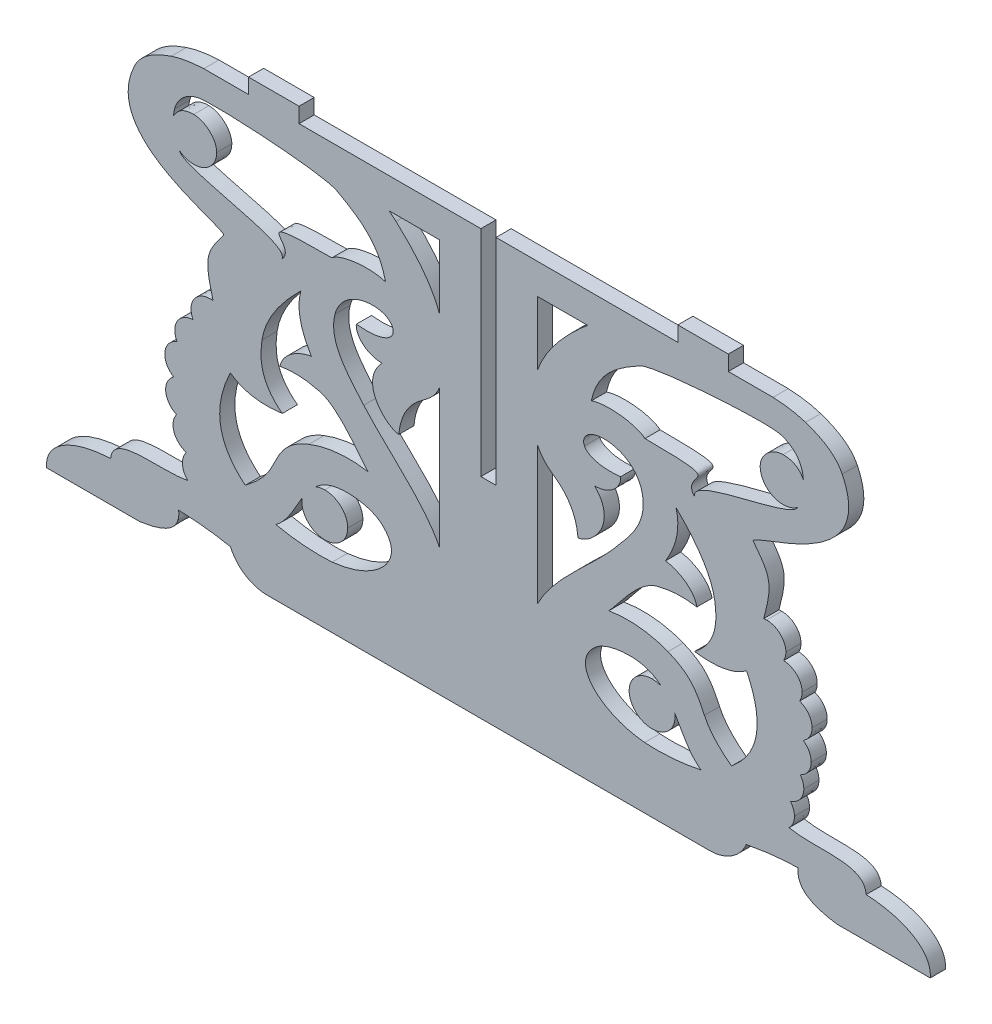
SolidWorks part; units mm, degrees
ref_plane "Plano frontal" through (0, 0, 0) normal (0, 0, 1) x (1, 0, 0)
ref_plane "Plano superior" through (0, 0, 0) normal (0, 1, 0) x (1, 0, 0)
ref_plane "Plano direito" through (0, 0, 0) normal (1, 0, 0) x (0, 0, -1)
sketch "Model" plane through (0, 0, 0) normal (0, 0, 1) x (1, 0, 0)
  line L0 (-58.0295, -71.5532) -> (-45.7155, -71.5532)
  line L1 (46.2957, -71.5532) -> (58.6097, -71.5532)
  line L2 (37.859, -15.5493) -> (31.9567, -15.5493)
  line L3 (31.9567, -15.5493) -> (31.9567, -13.5542)
  line L4 (31.9567, -13.5542) -> (25.2901, -13.5542)
  line L5 (25.2901, -13.5542) -> (25.2901, -15.5493)
  line L6 (25.2901, -15.5493) -> (1.2901, -15.5493)
  line L7 (1.2901, -15.5493) -> (1.2901, -43.8921)
  line L8 (1.2901, -43.8921) -> (-0.7099, -43.8921)
  line L9 (-0.7099, -43.8921) -> (-0.7099, -15.5493)
  line L10 (-0.7099, -15.5493) -> (-24.7099, -15.5493)
  line L11 (-24.7099, -15.5493) -> (-24.7099, -13.5542)
  line L12 (-24.7099, -13.5542) -> (-31.3766, -13.5542)
  line L13 (-31.3766, -13.5542) -> (-31.3766, -15.5493)
  line L14 (-31.3766, -15.5493) -> (-37.2789, -15.5493)
  line L15 (41.8464, -22.9309) -> (41.8509, -22.9067)
  line L16 (27.4601, -32.0549) -> (27.5114, -32.0551)
  line L17 (6.7678, -54.6917) -> (6.7678, -36.4907)
  line L18 (25.2636, -34.7621) -> (25.2605, -34.7639)
  line L19 (25.2605, -34.7639) -> (25.2233, -34.7226)
  line L20 (6.7678, -27.9915) -> (6.7678, -19.5605)
  line L21 (6.7678, -19.5605) -> (13.3925, -19.5605)
  line L22 (-41.2663, -22.9309) -> (-41.2707, -22.9067)
  line L23 (-26.8799, -32.0549) -> (-26.9313, -32.0551)
  line L24 (-6.1877, -54.6917) -> (-6.1877, -36.4907)
  line L25 (-24.6834, -34.7621) -> (-24.6804, -34.7639)
  line L26 (-24.6804, -34.7639) -> (-24.6431, -34.7226)
  line L27 (-6.1877, -27.9915) -> (-6.1877, -19.5605)
  line L28 (-6.1877, -19.5605) -> (-12.8123, -19.5605)
  spline S0 degree 3 poles (-37.2789, -15.5493) (-38.8553, -15.6137) (-40.3345, -15.8508) (-41.5726, -16.2641) knots 0 0 0 0 0.016393 0.016393 0.016393 0.016393
  spline S1 degree 3 poles (-41.5726, -16.2641) (-44.2957, -17.1731) (-45.7419, -18.394) (-46.408, -19.7647) knots 0.016393 0.016393 0.016393 0.016393 0.032787 0.032787 0.032787 0.032787
  spline S2 degree 3 poles (-46.408, -19.7647) (-50.9976, -29.2085) (-35.6947, -31.9971) (-34.6325, -33.2356) knots 0.032787 0.032787 0.032787 0.032787 0.04918 0.04918 0.04918 0.04918
  spline S3 degree 3 poles (-34.6325, -33.2356) (-36.8968, -36.2087) (-37.3095, -36.8147) (-36.0561, -41.4551) knots 0.04918 0.04918 0.04918 0.04918 0.065574 0.065574 0.065574 0.065574
  spline S4 degree 3 poles (-36.0561, -41.4551) (-36.178, -41.4381) (-36.3027, -41.4292) (-36.4296, -41.4292) knots 0.065574 0.065574 0.065574 0.065574 0.081967 0.081967 0.081967 0.081967
  spline S5 degree 3 poles (-36.4296, -41.4292) (-37.8337, -41.4292) (-38.9723, -42.5045) (-38.9723, -43.8303) knots 0.081967 0.081967 0.081967 0.081967 0.098361 0.098361 0.098361 0.098361
  spline S6 degree 3 poles (-38.9723, -43.8303) (-38.9723, -44.2332) (-38.8669, -44.6128) (-38.681, -44.9462) knots 0.098361 0.098361 0.098361 0.098361 0.114754 0.114754 0.114754 0.114754
  spline S7 degree 3 poles (-38.681, -44.9462) (-40.0347, -44.9999) (-41.1152, -46.0535) (-41.1152, -47.3449) knots 0.114754 0.114754 0.114754 0.114754 0.131148 0.131148 0.131148 0.131148
  spline S8 degree 3 poles (-41.1152, -47.3449) (-41.1152, -47.7683) (-40.9989, -48.1658) (-40.7951, -48.5111) knots 0.131148 0.131148 0.131148 0.131148 0.147541 0.147541 0.147541 0.147541
  spline S9 degree 3 poles (-40.7951, -48.5111) (-41.7518, -48.856) (-42.4316, -49.7306) (-42.4316, -50.755) knots 0.147541 0.147541 0.147541 0.147541 0.163934 0.163934 0.163934 0.163934
  spline S10 degree 3 poles (-42.4316, -50.755) (-42.4316, -51.6062) (-41.9621, -52.3535) (-41.2547, -52.78) knots 0.163934 0.163934 0.163934 0.163934 0.180328 0.180328 0.180328 0.180328
  spline S11 degree 3 poles (-41.2547, -52.78) (-41.8988, -53.2156) (-42.3188, -53.9284) (-42.3188, -54.7333) knots 0.180328 0.180328 0.180328 0.180328 0.196721 0.196721 0.196721 0.196721
  spline S12 degree 3 poles (-42.3188, -54.7333) (-42.3188, -55.6878) (-41.7284, -56.5121) (-40.874, -56.899) knots 0.196721 0.196721 0.196721 0.196721 0.213115 0.213115 0.213115 0.213115
  spline S13 degree 3 poles (-40.874, -56.899) (-41.1678, -57.2907) (-41.3407, -57.7691) (-41.3407, -58.2855) knots 0.213115 0.213115 0.213115 0.213115 0.229508 0.229508 0.229508 0.229508
  spline S14 degree 3 poles (-41.3407, -58.2855) (-41.3407, -59.3557) (-40.5988, -60.2622) (-39.5745, -60.5722) knots 0.229508 0.229508 0.229508 0.229508 0.245902 0.245902 0.245902 0.245902
  spline S15 degree 3 poles (-39.5745, -60.5722) (-39.9035, -60.9769) (-40.0993, -61.4833) (-40.0993, -62.0328) knots 0.245902 0.245902 0.245902 0.245902 0.262295 0.262295 0.262295 0.262295
  spline S16 degree 3 poles (-40.0993, -62.0328) (-40.0993, -62.6755) (-39.8315, -63.2593) (-39.3959, -63.6903) knots 0.262295 0.262295 0.262295 0.262295 0.278689 0.278689 0.278689 0.278689
  spline S17 degree 3 poles (-39.3959, -63.6903) (-43.0969, -64.4482) (-49.2885, -62.8619) (-49.5679, -66.2516) knots 0.278689 0.278689 0.278689 0.278689 0.295082 0.295082 0.295082 0.295082
  spline S18 degree 3 poles (-49.5679, -66.2516) (-55.0145, -66.5289) (-58.2823, -68.7212) (-58.0295, -71.5532) knots 0.295082 0.295082 0.295082 0.295082 0.311475 0.311475 0.311475 0.311475
  spline S19 degree 3 poles (-45.7155, -71.5532) (-42.3585, -71.0822) (-40.3248, -69.9761) (-40.6026, -67.6718) knots 0.327869 0.327869 0.327869 0.327869 0.344262 0.344262 0.344262 0.344262
  spline S20 degree 3 poles (-40.6026, -67.6718) (-37.8869, -67.763) (-35.6926, -68.0475) (-33.7519, -68.4372) knots 0.344262 0.344262 0.344262 0.344262 0.360656 0.360656 0.360656 0.360656
  spline S21 degree 3 poles (-33.7519, -68.4372) (-32.9718, -70.2591) (-31.0759, -71.5532) (-28.8751, -71.5532) knots 0.360656 0.360656 0.360656 0.360656 0.377049 0.377049 0.377049 0.377049
  spline S22 degree 3 poles (-28.8751, -71.5532) (-9.4317, -71.5532) (10.0118, -71.5532) (29.4553, -71.5532) knots 0.377049 0.377049 0.377049 0.377049 0.393443 0.393443 0.393443 0.393443
  spline S23 degree 3 poles (29.4553, -71.5532) (31.6561, -71.5532) (33.552, -70.2591) (34.3321, -68.4372) knots 0.393443 0.393443 0.393443 0.393443 0.409836 0.409836 0.409836 0.409836
  spline S24 degree 3 poles (34.3321, -68.4372) (36.2728, -68.0475) (38.4671, -67.763) (41.1827, -67.6718) knots 0.409836 0.409836 0.409836 0.409836 0.42623 0.42623 0.42623 0.42623
  spline S25 degree 3 poles (41.1827, -67.6718) (40.905, -69.9761) (42.9386, -71.0822) (46.2957, -71.5532) knots 0.42623 0.42623 0.42623 0.42623 0.442623 0.442623 0.442623 0.442623
  spline S26 degree 3 poles (58.6097, -71.5532) (58.8625, -68.7212) (55.5947, -66.5289) (50.1481, -66.2516) knots 0.459016 0.459016 0.459016 0.459016 0.47541 0.47541 0.47541 0.47541
  spline S27 degree 3 poles (50.1481, -66.2516) (49.8687, -62.8619) (43.6771, -64.4482) (39.976, -63.6903) knots 0.47541 0.47541 0.47541 0.47541 0.491803 0.491803 0.491803 0.491803
  spline S28 degree 3 poles (39.976, -63.6903) (40.4117, -63.2593) (40.6794, -62.6755) (40.6794, -62.0328) knots 0.491803 0.491803 0.491803 0.491803 0.508197 0.508197 0.508197 0.508197
  spline S29 degree 3 poles (40.6794, -62.0328) (40.6794, -61.4833) (40.4836, -60.9769) (40.1546, -60.5722) knots 0.508197 0.508197 0.508197 0.508197 0.52459 0.52459 0.52459 0.52459
  spline S30 degree 3 poles (40.1546, -60.5722) (41.1789, -60.2622) (41.9209, -59.3557) (41.9209, -58.2855) knots 0.52459 0.52459 0.52459 0.52459 0.540984 0.540984 0.540984 0.540984
  spline S31 degree 3 poles (41.9209, -58.2855) (41.9209, -57.7691) (41.748, -57.2907) (41.4541, -56.899) knots 0.540984 0.540984 0.540984 0.540984 0.557377 0.557377 0.557377 0.557377
  spline S32 degree 3 poles (41.4541, -56.899) (42.3085, -56.5121) (42.8989, -55.6878) (42.8989, -54.7333) knots 0.557377 0.557377 0.557377 0.557377 0.57377 0.57377 0.57377 0.57377
  spline S33 degree 3 poles (42.8989, -54.7333) (42.8989, -53.9284) (42.4789, -53.2156) (41.8349, -52.78) knots 0.57377 0.57377 0.57377 0.57377 0.590164 0.590164 0.590164 0.590164
  spline S34 degree 3 poles (41.8349, -52.78) (42.5423, -52.3535) (43.0118, -51.6062) (43.0118, -50.755) knots 0.590164 0.590164 0.590164 0.590164 0.606557 0.606557 0.606557 0.606557
  spline S35 degree 3 poles (43.0118, -50.755) (43.0118, -49.7306) (42.3319, -48.856) (41.3753, -48.5111) knots 0.606557 0.606557 0.606557 0.606557 0.622951 0.622951 0.622951 0.622951
  spline S36 degree 3 poles (41.3753, -48.5111) (41.5791, -48.1658) (41.6954, -47.7683) (41.6954, -47.3449) knots 0.622951 0.622951 0.622951 0.622951 0.639344 0.639344 0.639344 0.639344
  spline S37 degree 3 poles (41.6954, -47.3449) (41.6954, -46.0535) (40.6149, -44.9999) (39.2612, -44.9462) knots 0.639344 0.639344 0.639344 0.639344 0.655738 0.655738 0.655738 0.655738
  spline S38 degree 3 poles (39.2612, -44.9462) (39.447, -44.6128) (39.5524, -44.2332) (39.5524, -43.8303) knots 0.655738 0.655738 0.655738 0.655738 0.672131 0.672131 0.672131 0.672131
  spline S39 degree 3 poles (39.5524, -43.8303) (39.5524, -42.5045) (38.4138, -41.4292) (37.0097, -41.4292) knots 0.672131 0.672131 0.672131 0.672131 0.688525 0.688525 0.688525 0.688525
  spline S40 degree 3 poles (37.0097, -41.4292) (36.8829, -41.4292) (36.7582, -41.4381) (36.6363, -41.4551) knots 0.688525 0.688525 0.688525 0.688525 0.704918 0.704918 0.704918 0.704918
  spline S41 degree 3 poles (36.6363, -41.4551) (37.8897, -36.8147) (37.477, -36.2087) (35.2126, -33.2356) knots 0.704918 0.704918 0.704918 0.704918 0.721311 0.721311 0.721311 0.721311
  spline S42 degree 3 poles (35.2126, -33.2356) (36.2749, -31.9971) (51.5777, -29.2085) (46.9881, -19.7647) knots 0.721311 0.721311 0.721311 0.721311 0.737705 0.737705 0.737705 0.737705
  spline S43 degree 3 poles (46.9881, -19.7647) (46.322, -18.394) (44.8758, -17.1731) (42.1528, -16.2641) knots 0.737705 0.737705 0.737705 0.737705 0.754098 0.754098 0.754098 0.754098
  spline S44 degree 3 poles (42.1528, -16.2641) (40.9147, -15.8508) (39.4354, -15.6137) (37.859, -15.5493) knots 0.754098 0.754098 0.754098 0.754098 0.770492 0.770492 0.770492 0.770492
  spline S45 degree 3 poles (41.0991, -26.5055) (40.5779, -26.9077) (39.9123, -27.1488) (39.1869, -27.1489) knots 0 0 0 0 0.071429 0.071429 0.071429 0.071429
  spline S46 degree 3 poles (39.1869, -27.1489) (37.5166, -27.1488) (36.162, -25.8701) (36.162, -24.2928) knots 0.071429 0.071429 0.071429 0.071429 0.142857 0.142857 0.142857 0.142857
  spline S47 degree 3 poles (36.162, -24.2928) (36.162, -22.7154) (37.7777, -21.4359) (39.1869, -21.4359) knots 0.142857 0.142857 0.142857 0.142857 0.214286 0.214286 0.214286 0.214286
  spline S48 degree 3 poles (39.1869, -21.4359) (40.5962, -21.4359) (41.3341, -22.0405) (41.8464, -22.9309) knots 0.214286 0.214286 0.214286 0.214286 0.285714 0.285714 0.285714 0.285714
  spline S49 degree 3 poles (41.8509, -22.9067) (41.8313, -22.6217) (41.7887, -22.3443) (41.7202, -22.0779) knots 0.357143 0.357143 0.357143 0.357143 0.428571 0.428571 0.428571 0.428571
  spline S50 degree 3 poles (41.7202, -22.0779) (41.4272, -20.9402) (40.448, -19.6292) (38.5962, -19.2465) knots 0.428571 0.428571 0.428571 0.428571 0.5 0.5 0.5 0.5
  spline S51 degree 3 poles (38.5962, -19.2465) (36.406, -18.7935) (22.1887, -19.664) (20.2699, -20.7424) knots 0.5 0.5 0.5 0.5 0.571429 0.571429 0.571429 0.571429
  spline S52 degree 3 poles (20.2699, -20.7424) (17.8156, -22.1218) (14.7391, -23.8156) (13.8733, -27.9378) knots 0.571429 0.571429 0.571429 0.571429 0.642857 0.642857 0.642857 0.642857
  spline S53 degree 3 poles (13.8733, -27.9378) (15.6554, -27.278) (19.6405, -27.5829) (20.951, -28.7164) knots 0.642857 0.642857 0.642857 0.642857 0.714286 0.714286 0.714286 0.714286
  spline S54 degree 3 poles (20.951, -28.7164) (32.8615, -28.7164) (25.4889, -29.6957) (27.4601, -32.0549) knots 0.714286 0.714286 0.714286 0.714286 0.785714 0.785714 0.785714 0.785714
  spline S55 degree 3 poles (27.5114, -32.0551) (26.8882, -29.8021) (40.2299, -28.4327) (41.0991, -26.5055) knots 0.857143 0.857143 0.857143 0.857143 1 1 1 1
  spline S56 degree 3 poles (6.7678, -36.4907) (7.1177, -37.3515) (7.7821, -38.1712) (8.8217, -38.8882) knots 0.083333 0.083333 0.083333 0.083333 0.166667 0.166667 0.166667 0.166667
  spline S57 degree 3 poles (8.8217, -38.8882) (10.4062, -39.9811) (11.8709, -41.6153) (12.1135, -44.4942) knots 0.166667 0.166667 0.166667 0.166667 0.25 0.25 0.25 0.25
  spline S58 degree 3 poles (12.1135, -44.4942) (14.0789, -44.2506) (17.4305, -40.5964) (14.3074, -37.4419) knots 0.25 0.25 0.25 0.25 0.333333 0.333333 0.333333 0.333333
  spline S59 degree 3 poles (14.3074, -37.4419) (16.2667, -37.4909) (17.8601, -36.0383) (17.7312, -34.6895) knots 0.333333 0.333333 0.333333 0.333333 0.416667 0.416667 0.416667 0.416667
  spline S60 degree 3 poles (17.7312, -34.6895) (14.9058, -34.9858) (13.3648, -34.3445) (12.9675, -33.5507) knots 0.416667 0.416667 0.416667 0.416667 0.5 0.5 0.5 0.5
  spline S61 degree 3 poles (12.9675, -33.5507) (12.7751, -33.1662) (12.8359, -32.7459) (13.1165, -32.3713) knots 0.5 0.5 0.5 0.5 0.583333 0.583333 0.583333 0.583333
  spline S62 degree 3 poles (13.1165, -32.3713) (13.9625, -31.2424) (16.199, -31.233) (17.7583, -31.8726) knots 0.583333 0.583333 0.583333 0.583333 0.666667 0.666667 0.666667 0.666667
  spline S63 degree 3 poles (17.7583, -31.8726) (19.301, -32.5053) (20.2207, -33.6838) (20.5427, -34.9484) knots 0.666667 0.666667 0.666667 0.666667 0.75 0.75 0.75 0.75
  spline S64 degree 3 poles (20.5427, -34.9484) (21.4025, -38.3248) (19.0104, -40.8664) (16.7475, -43.4634) knots 0.75 0.75 0.75 0.75 0.833333 0.833333 0.833333 0.833333
  spline S65 degree 3 poles (16.7475, -43.4634) (13.6063, -47.0685) (8.8067, -50.5847) (6.7678, -54.6917) knots 0.833333 0.833333 0.833333 0.833333 1 1 1 1
  spline S66 degree 3 poles (25.2233, -34.7226) (25.1662, -34.6668) (25.1087, -34.611) (25.0509, -34.555) knots 0.133333 0.133333 0.133333 0.133333 0.2 0.2 0.2 0.2
  spline S67 degree 3 poles (25.0509, -34.555) (25.6852, -36.9016) (25.0055, -39.1271) (23.6733, -41.332) knots 0.2 0.2 0.2 0.2 0.266667 0.266667 0.266667 0.266667
  spline S68 degree 3 poles (23.6733, -41.332) (25.5011, -41.6329) (27.4577, -42.8346) (27.8065, -44.5414) knots 0.266667 0.266667 0.266667 0.266667 0.333333 0.333333 0.333333 0.333333
  spline S69 degree 3 poles (27.8065, -44.5414) (26.0758, -44.234) (24.4417, -44.3248) (22.61, -44.7856) knots 0.333333 0.333333 0.333333 0.333333 0.4 0.4 0.4 0.4
  spline S70 degree 3 poles (22.61, -44.7856) (19.945, -45.4561) (17.4208, -49.5455) (16.1735, -50.7932) knots 0.4 0.4 0.4 0.4 0.466667 0.466667 0.466667 0.466667
  spline S71 degree 3 poles (16.1735, -50.7932) (19.0564, -50.2753) (21.8473, -50.7043) (23.993, -51.5534) knots 0.466667 0.466667 0.466667 0.466667 0.533333 0.533333 0.533333 0.533333
  spline S72 degree 3 poles (23.993, -51.5534) (27.0207, -52.7513) (27.8131, -54.3528) (28.7997, -56.4207) knots 0.533333 0.533333 0.533333 0.533333 0.6 0.6 0.6 0.6
  spline S73 degree 3 poles (28.7997, -56.4207) (29.3141, -57.4989) (30.133, -58.7455) (32.3886, -60.4342) knots 0.6 0.6 0.6 0.6 0.666667 0.666667 0.666667 0.666667
  spline S74 degree 3 poles (32.3886, -60.4342) (35.742, -57.6622) (36.9574, -53.9478) (34.3619, -48.5537) knots 0.666667 0.666667 0.666667 0.666667 0.733333 0.733333 0.733333 0.733333
  spline S75 degree 3 poles (34.3619, -48.5537) (32.6868, -49.8379) (30.2026, -50.1725) (27.4986, -49.7829) knots 0.733333 0.733333 0.733333 0.733333 0.8 0.8 0.8 0.8
  spline S76 degree 3 poles (27.4986, -49.7829) (30.2732, -47.6893) (30.5616, -45.1772) (30.1795, -42.7182) knots 0.8 0.8 0.8 0.8 0.866667 0.866667 0.866667 0.866667
  spline S77 degree 3 poles (30.1795, -42.7182) (29.7867, -40.1904) (28.096, -37.5453) (25.2636, -34.7621) knots 0.866667 0.866667 0.866667 0.866667 1 1 1 1
  spline S78 degree 3 poles (21.8901, -55.715) (20.2198, -55.715) (18.8652, -56.9943) (18.8652, -58.5718) knots 0 0 0 0 0.090909 0.090909 0.090909 0.090909
  spline S79 degree 3 poles (18.8652, -58.5718) (18.8652, -60.1489) (20.2198, -61.4279) (21.8901, -61.4279) knots 0.090909 0.090909 0.090909 0.090909 0.181818 0.181818 0.181818 0.181818
  spline S80 degree 3 poles (21.8901, -61.4279) (23.5605, -61.4279) (24.915, -60.1489) (24.915, -58.5718) knots 0.181818 0.181818 0.181818 0.181818 0.272727 0.272727 0.272727 0.272727
  spline S81 degree 3 poles (24.915, -58.5718) (24.915, -58.4174) (24.9018, -58.266) (24.8768, -58.1185) knots 0.272727 0.272727 0.272727 0.272727 0.363636 0.363636 0.363636 0.363636
  spline S82 degree 3 poles (24.8768, -58.1185) (25.9318, -59.8199) (26.7068, -61.7087) (28.3424, -62.8978) knots 0.363636 0.363636 0.363636 0.363636 0.454545 0.454545 0.454545 0.454545
  spline S83 degree 3 poles (28.3424, -62.8978) (25.7833, -63.5044) (22.5117, -63.6304) (20.911, -63.4825) knots 0.454545 0.454545 0.454545 0.454545 0.545455 0.545455 0.545455 0.545455
  spline S84 degree 3 poles (20.911, -63.4825) (15.1322, -62.9483) (10.6438, -58.8213) (14.5848, -55.7043) knots 0.545455 0.545455 0.545455 0.545455 0.636364 0.636364 0.636364 0.636364
  spline S85 degree 3 poles (14.5848, -55.7043) (16.0936, -54.5109) (19.8733, -54.0372) (22.0533, -55.2269) knots 0.636364 0.636364 0.636364 0.636364 0.727273 0.727273 0.727273 0.727273
  spline S86 degree 3 poles (22.0533, -55.2269) (22.4453, -55.4408) (22.7943, -55.6868) (23.1104, -55.9573) knots 0.727273 0.727273 0.727273 0.727273 0.818182 0.818182 0.818182 0.818182
  spline S87 degree 3 poles (23.1104, -55.9573) (22.7371, -55.8016) (22.3244, -55.715) (21.8901, -55.715) knots 0.818182 0.818182 0.818182 0.818182 1 1 1 1
  spline S88 degree 3 poles (13.3925, -19.5605) (13.0822, -19.8065) (12.7813, -20.0607) (12.4899, -20.3228) knots 0.4 0.4 0.4 0.4 0.6 0.6 0.6 0.6
  spline S89 degree 3 poles (12.4899, -20.3228) (9.9255, -22.6296) (7.6953, -25.2917) (6.7678, -27.9915) knots 0.6 0.6 0.6 0.6 1 1 1 1
  spline S90 degree 3 poles (-40.5189, -26.5055) (-39.9977, -26.9077) (-39.3321, -27.1488) (-38.6068, -27.1489) knots 0 0 0 0 0.071429 0.071429 0.071429 0.071429
  spline S91 degree 3 poles (-38.6068, -27.1489) (-36.9365, -27.1488) (-35.5819, -25.8701) (-35.5819, -24.2928) knots 0.071429 0.071429 0.071429 0.071429 0.142857 0.142857 0.142857 0.142857
  spline S92 degree 3 poles (-35.5819, -24.2928) (-35.5819, -22.7154) (-37.1975, -21.4359) (-38.6068, -21.4359) knots 0.142857 0.142857 0.142857 0.142857 0.214286 0.214286 0.214286 0.214286
  spline S93 degree 3 poles (-38.6068, -21.4359) (-40.016, -21.4359) (-40.754, -22.0405) (-41.2663, -22.9309) knots 0.214286 0.214286 0.214286 0.214286 0.285714 0.285714 0.285714 0.285714
  spline S94 degree 3 poles (-41.2707, -22.9067) (-41.2511, -22.6217) (-41.2086, -22.3443) (-41.14, -22.0779) knots 0.357143 0.357143 0.357143 0.357143 0.428571 0.428571 0.428571 0.428571
  spline S95 degree 3 poles (-41.14, -22.0779) (-40.847, -20.9402) (-39.8679, -19.6292) (-38.0161, -19.2465) knots 0.428571 0.428571 0.428571 0.428571 0.5 0.5 0.5 0.5
  spline S96 degree 3 poles (-38.0161, -19.2465) (-35.8259, -18.7935) (-21.6086, -19.664) (-19.6898, -20.7424) knots 0.5 0.5 0.5 0.5 0.571429 0.571429 0.571429 0.571429
  spline S97 degree 3 poles (-19.6898, -20.7424) (-17.2355, -22.1218) (-14.1589, -23.8156) (-13.2931, -27.9378) knots 0.571429 0.571429 0.571429 0.571429 0.642857 0.642857 0.642857 0.642857
  spline S98 degree 3 poles (-13.2931, -27.9378) (-15.0753, -27.278) (-19.0603, -27.5829) (-20.3708, -28.7164) knots 0.642857 0.642857 0.642857 0.642857 0.714286 0.714286 0.714286 0.714286
  spline S99 degree 3 poles (-20.3708, -28.7164) (-32.2813, -28.7164) (-24.9088, -29.6957) (-26.8799, -32.0549) knots 0.714286 0.714286 0.714286 0.714286 0.785714 0.785714 0.785714 0.785714
  spline S100 degree 3 poles (-26.9313, -32.0551) (-26.308, -29.8021) (-39.6497, -28.4327) (-40.5189, -26.5055) knots 0.857143 0.857143 0.857143 0.857143 1 1 1 1
  spline S101 degree 3 poles (-6.1877, -36.4907) (-6.5375, -37.3515) (-7.202, -38.1712) (-8.2415, -38.8882) knots 0.083333 0.083333 0.083333 0.083333 0.166667 0.166667 0.166667 0.166667
  spline S102 degree 3 poles (-8.2415, -38.8882) (-9.826, -39.9811) (-11.2907, -41.6153) (-11.5334, -44.4942) knots 0.166667 0.166667 0.166667 0.166667 0.25 0.25 0.25 0.25
  spline S103 degree 3 poles (-11.5334, -44.4942) (-13.4988, -44.2506) (-16.8504, -40.5964) (-13.7272, -37.4419) knots 0.25 0.25 0.25 0.25 0.333333 0.333333 0.333333 0.333333
  spline S104 degree 3 poles (-13.7272, -37.4419) (-15.6865, -37.4909) (-17.2799, -36.0383) (-17.151, -34.6895) knots 0.333333 0.333333 0.333333 0.333333 0.416667 0.416667 0.416667 0.416667
  spline S105 degree 3 poles (-17.151, -34.6895) (-14.3257, -34.9858) (-12.7846, -34.3445) (-12.3874, -33.5507) knots 0.416667 0.416667 0.416667 0.416667 0.5 0.5 0.5 0.5
  spline S106 degree 3 poles (-12.3874, -33.5507) (-12.195, -33.1662) (-12.2557, -32.7459) (-12.5364, -32.3713) knots 0.5 0.5 0.5 0.5 0.583333 0.583333 0.583333 0.583333
  spline S107 degree 3 poles (-12.5364, -32.3713) (-13.3823, -31.2424) (-15.6188, -31.233) (-17.1782, -31.8726) knots 0.583333 0.583333 0.583333 0.583333 0.666667 0.666667 0.666667 0.666667
  spline S108 degree 3 poles (-17.1782, -31.8726) (-18.7209, -32.5053) (-19.6406, -33.6838) (-19.9625, -34.9484) knots 0.666667 0.666667 0.666667 0.666667 0.75 0.75 0.75 0.75
  spline S109 degree 3 poles (-19.9625, -34.9484) (-20.8224, -38.3248) (-18.4302, -40.8664) (-16.1674, -43.4634) knots 0.75 0.75 0.75 0.75 0.833333 0.833333 0.833333 0.833333
  spline S110 degree 3 poles (-16.1674, -43.4634) (-13.0261, -47.0685) (-8.2265, -50.5847) (-6.1877, -54.6917) knots 0.833333 0.833333 0.833333 0.833333 1 1 1 1
  spline S111 degree 3 poles (-24.6431, -34.7226) (-24.5861, -34.6668) (-24.5286, -34.611) (-24.4707, -34.555) knots 0.133333 0.133333 0.133333 0.133333 0.2 0.2 0.2 0.2
  spline S112 degree 3 poles (-24.4707, -34.555) (-25.105, -36.9016) (-24.4253, -39.1271) (-23.0931, -41.332) knots 0.2 0.2 0.2 0.2 0.266667 0.266667 0.266667 0.266667
  spline S113 degree 3 poles (-23.0931, -41.332) (-24.921, -41.6329) (-26.8776, -42.8346) (-27.2264, -44.5414) knots 0.266667 0.266667 0.266667 0.266667 0.333333 0.333333 0.333333 0.333333
  spline S114 degree 3 poles (-27.2264, -44.5414) (-25.4957, -44.234) (-23.8615, -44.3248) (-22.0299, -44.7856) knots 0.333333 0.333333 0.333333 0.333333 0.4 0.4 0.4 0.4
  spline S115 degree 3 poles (-22.0299, -44.7856) (-19.3648, -45.4561) (-16.8406, -49.5455) (-15.5933, -50.7932) knots 0.4 0.4 0.4 0.4 0.466667 0.466667 0.466667 0.466667
  spline S116 degree 3 poles (-15.5933, -50.7932) (-18.4762, -50.2753) (-21.2671, -50.7043) (-23.4129, -51.5534) knots 0.466667 0.466667 0.466667 0.466667 0.533333 0.533333 0.533333 0.533333
  spline S117 degree 3 poles (-23.4129, -51.5534) (-26.4406, -52.7513) (-27.233, -54.3528) (-28.2196, -56.4207) knots 0.533333 0.533333 0.533333 0.533333 0.6 0.6 0.6 0.6
  spline S118 degree 3 poles (-28.2196, -56.4207) (-28.734, -57.4989) (-29.5528, -58.7455) (-31.8084, -60.4342) knots 0.6 0.6 0.6 0.6 0.666667 0.666667 0.666667 0.666667
  spline S119 degree 3 poles (-31.8084, -60.4342) (-35.1618, -57.6622) (-36.3773, -53.9478) (-33.7818, -48.5537) knots 0.666667 0.666667 0.666667 0.666667 0.733333 0.733333 0.733333 0.733333
  spline S120 degree 3 poles (-33.7818, -48.5537) (-32.1066, -49.8379) (-29.6224, -50.1725) (-26.9184, -49.7829) knots 0.733333 0.733333 0.733333 0.733333 0.8 0.8 0.8 0.8
  spline S121 degree 3 poles (-26.9184, -49.7829) (-29.693, -47.6893) (-29.9814, -45.1772) (-29.5994, -42.7182) knots 0.8 0.8 0.8 0.8 0.866667 0.866667 0.866667 0.866667
  spline S122 degree 3 poles (-29.5994, -42.7182) (-29.2066, -40.1904) (-27.5159, -37.5453) (-24.6834, -34.7621) knots 0.866667 0.866667 0.866667 0.866667 1 1 1 1
  spline S123 degree 3 poles (-21.3099, -55.715) (-19.6397, -55.715) (-18.2851, -56.9943) (-18.2851, -58.5718) knots 0 0 0 0 0.090909 0.090909 0.090909 0.090909
  spline S124 degree 3 poles (-18.2851, -58.5718) (-18.2851, -60.1489) (-19.6397, -61.4279) (-21.3099, -61.4279) knots 0.090909 0.090909 0.090909 0.090909 0.181818 0.181818 0.181818 0.181818
  spline S125 degree 3 poles (-21.3099, -61.4279) (-22.9803, -61.4279) (-24.3349, -60.1489) (-24.3349, -58.5718) knots 0.181818 0.181818 0.181818 0.181818 0.272727 0.272727 0.272727 0.272727
  spline S126 degree 3 poles (-24.3349, -58.5718) (-24.3349, -58.4174) (-24.3216, -58.266) (-24.2967, -58.1185) knots 0.272727 0.272727 0.272727 0.272727 0.363636 0.363636 0.363636 0.363636
  spline S127 degree 3 poles (-24.2967, -58.1185) (-25.3516, -59.8199) (-26.1266, -61.7087) (-27.7623, -62.8978) knots 0.363636 0.363636 0.363636 0.363636 0.454545 0.454545 0.454545 0.454545
  spline S128 degree 3 poles (-27.7623, -62.8978) (-25.2031, -63.5044) (-21.9316, -63.6304) (-20.3309, -63.4825) knots 0.454545 0.454545 0.454545 0.454545 0.545455 0.545455 0.545455 0.545455
  spline S129 degree 3 poles (-20.3309, -63.4825) (-14.552, -62.9483) (-10.0636, -58.8213) (-14.0046, -55.7043) knots 0.545455 0.545455 0.545455 0.545455 0.636364 0.636364 0.636364 0.636364
  spline S130 degree 3 poles (-14.0046, -55.7043) (-15.5134, -54.5109) (-19.2931, -54.0372) (-21.4731, -55.2269) knots 0.636364 0.636364 0.636364 0.636364 0.727273 0.727273 0.727273 0.727273
  spline S131 degree 3 poles (-21.4731, -55.2269) (-21.8651, -55.4408) (-22.2141, -55.6868) (-22.5303, -55.9573) knots 0.727273 0.727273 0.727273 0.727273 0.818182 0.818182 0.818182 0.818182
  spline S132 degree 3 poles (-22.5303, -55.9573) (-22.157, -55.8016) (-21.7442, -55.715) (-21.3099, -55.715) knots 0.818182 0.818182 0.818182 0.818182 1 1 1 1
  spline S133 degree 3 poles (-12.8123, -19.5605) (-12.5021, -19.8065) (-12.2011, -20.0607) (-11.9097, -20.3228) knots 0.4 0.4 0.4 0.4 0.6 0.6 0.6 0.6
  spline S134 degree 3 poles (-11.9097, -20.3228) (-9.3454, -22.6296) (-7.1151, -25.2917) (-6.1877, -27.9915) knots 0.6 0.6 0.6 0.6 1 1 1 1
extrude "Ressalto-extrusão1" add sketch "Model" along normal blind 2
